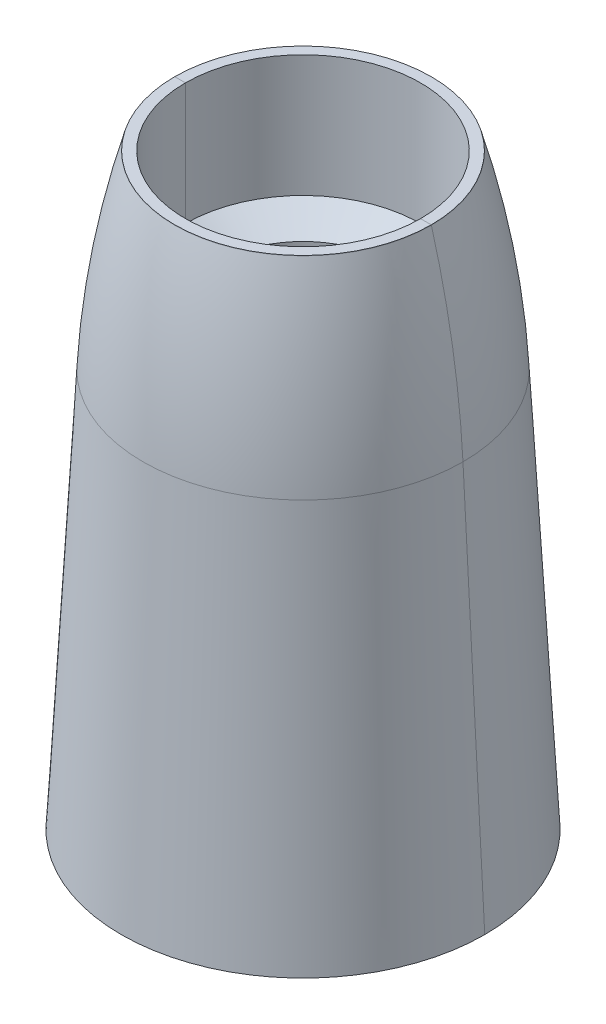
SolidWorks part; units mm, degrees
ref_plane "Front Plane" through (0, 0, 0) normal (0, 0, 1) x (1, 0, 0)
ref_plane "Top Plane" through (0, 0, 0) normal (0, 1, 0) x (1, 0, 0)
ref_plane "Right Plane" through (0, 0, 0) normal (1, 0, 0) x (0, 0, -1)
sketch "Sketch1" plane through (0, 0, 0) normal (1, 0, 0) x (0, 0, -1)
  line L0 (0, 0) -> (0, 12.1024) construction
  line L1 (2.6, 0) -> (8.5, 0)
  line L2 (2.6, 0) -> (2.6, 8)
  line L3 (2.6, 8) -> (5.5, 8)
  line L6 (4, 14.5) -> (4, 21)
  line L9 (5.5, 27.5) -> (6, 27.5)
  line L11 (7.2356, 23.1454) -> (8.5, 0)
  line L14 (6, 27.5) -> (7.2356, 23.1454)
  line L15 (5.5, 27.5) -> (5.5, 21.8)
  line L16 (5.5, 21.8) -> (4, 21)
  line L17 (5.5, 8) -> (5.5, 13.7)
  line L18 (5.5, 13.7) -> (4, 14.5)
  dimension "D1" = 2.6
  dimension "D2" = 5.9
  dimension "D3" = 8
  dimension "D4" = 0.5
  dimension "D5" = 5.7
  dimension "D6" = 19.5
  dimension "D7" = 6.5
  dimension "D8" = 4
revolve "Revolve1" add sketch "Sketch1" angle 360 about L0
fillet "Fillet1" radius 40.5 1 edges at (0, 23.1454, -7.2356)
split "Split1" trim tools "Front Plane" bodies to split 101 resulting bodies 102 103
